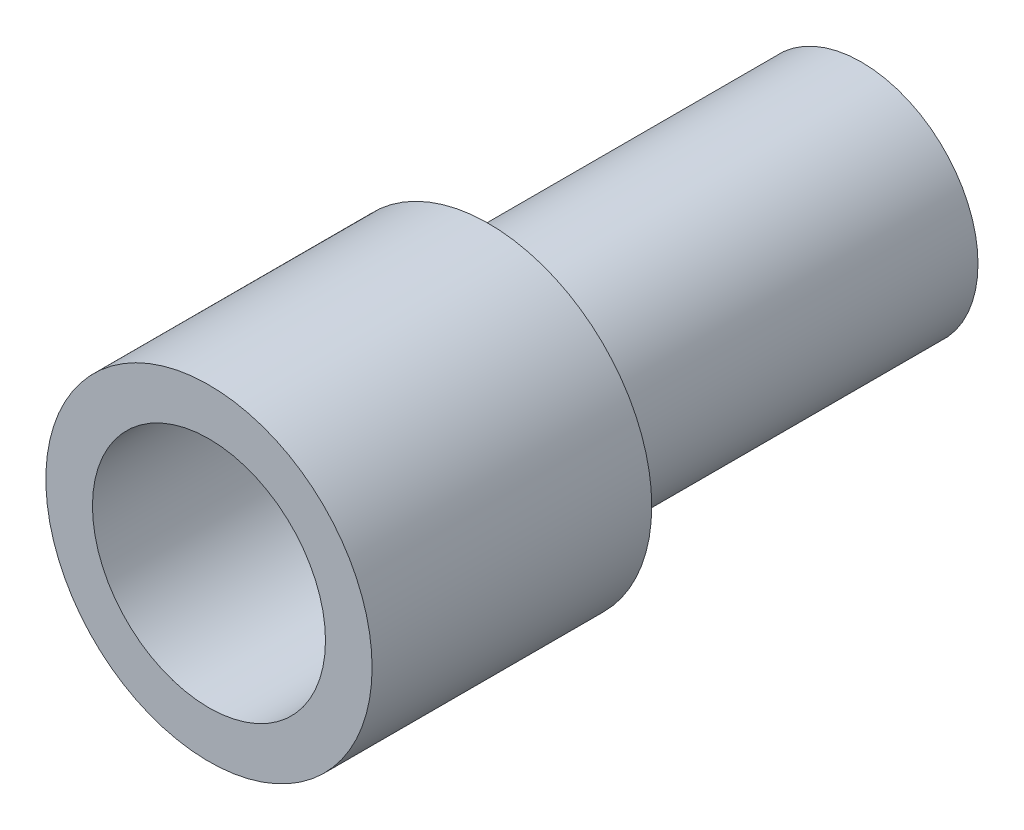
SolidWorks part; units mm, degrees
ref_plane "Plan de face" through (0, 0, 0) normal (0, 0, 1) x (1, 0, 0)
ref_plane "Plan de dessus" through (0, 0, 0) normal (0, 1, 0) x (1, 0, 0)
ref_plane "Plan de droite" through (0, 0, 0) normal (1, 0, 0) x (0, 0, -1)
sketch "Esquisse1" plane through (0, 0, 0) normal (0, 0, 1) x (1, 0, 0)
  circle A0 centre (0, 0) radius 3.5
  point P3 (0, 0)
  dimension "D1" = 7
extrude "Boss.-Extru.2" add sketch "Esquisse1" along normal blind 6
sketch "Esquisse3" plane through (0, 0, 6) normal (0, 0, 1) x (1, 0, 0)
  circle A0 centre (0, 0) radius 2.5
extrude "Enlèv. mat.-Extru.1" cut sketch "Esquisse3" against normal blind 5
sketch "Esquisse4" plane through (0, 0, 0) normal (0, 0, -1) x (-1, 0, 0)
  circle A0 centre (0, 0) radius 2.5
extrude "Boss.-Extru.3" add sketch "Esquisse4" along normal blind 8
